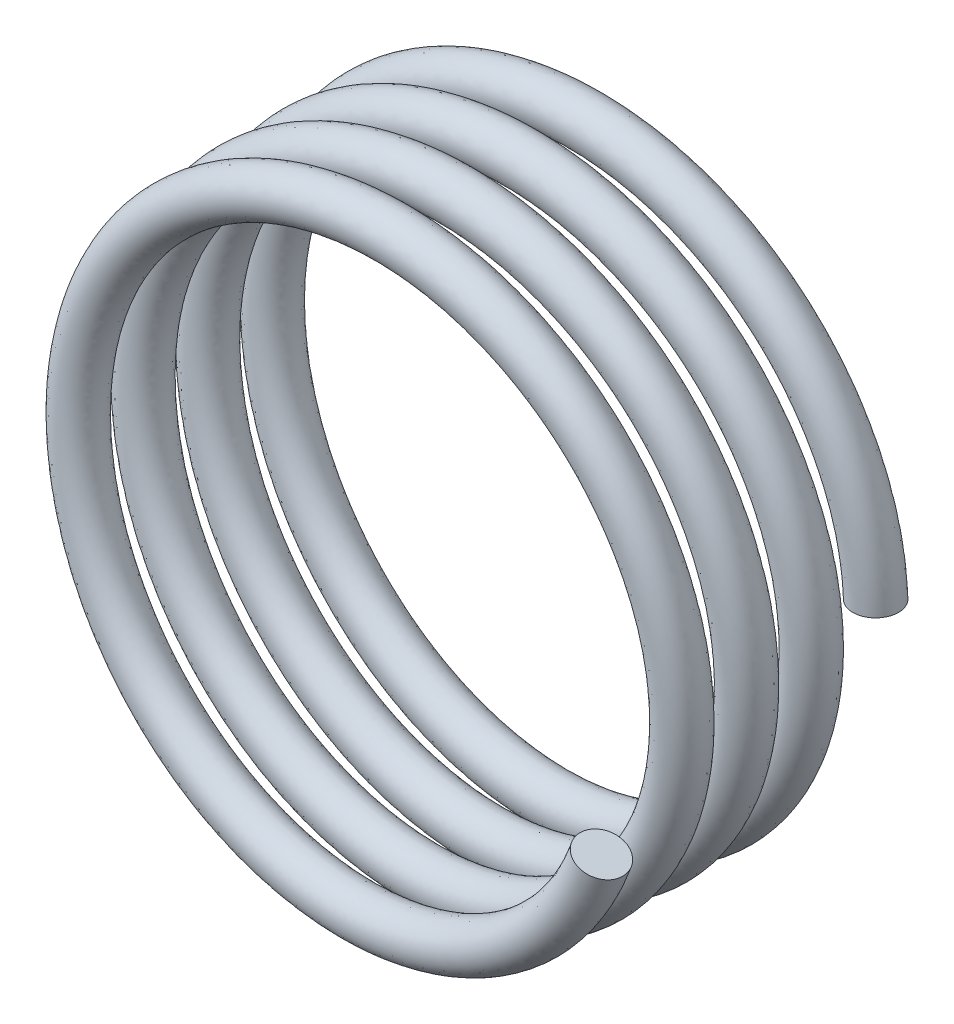
SolidWorks part; units mm, degrees
material "Acero aleado"
ref_plane "Alzado" through (0, 0, 0) normal (0, 0, 1) x (1, 0, 0)
ref_plane "Planta" through (0, 0, 0) normal (0, 1, 0) x (1, 0, 0)
ref_plane "Vista lateral" through (0, 0, 0) normal (1, 0, 0) x (0, 0, -1)
ref_plane "Plano1" through (0, 0, 115.1039) normal (0, 0, 1) x (1, 0, 0)
sketch "Sk_Helice_Muelle_B" plane through (0, 0, 115.1039) normal (0, 0, 1) x (1, 0, 0)
  circle A0 centre (-6, -26) radius 7.5
curve "Helice_Muelle_B" pitch 1.7 height 6.7 turns 3.9412
ref_plane "Plano3" through (0, -26, 0) normal (0, 1, 0) x (1, 0, 0)
sketch "Sk_alambre" plane through (0, -26, 0) normal (0, 1, 0) x (1, 0, 0)
  circle A0 centre (1.5, -55) radius 0.6
sweep "Muelle_B" add profiles "Sk_alambre" path "Helice_Muelle_B"
